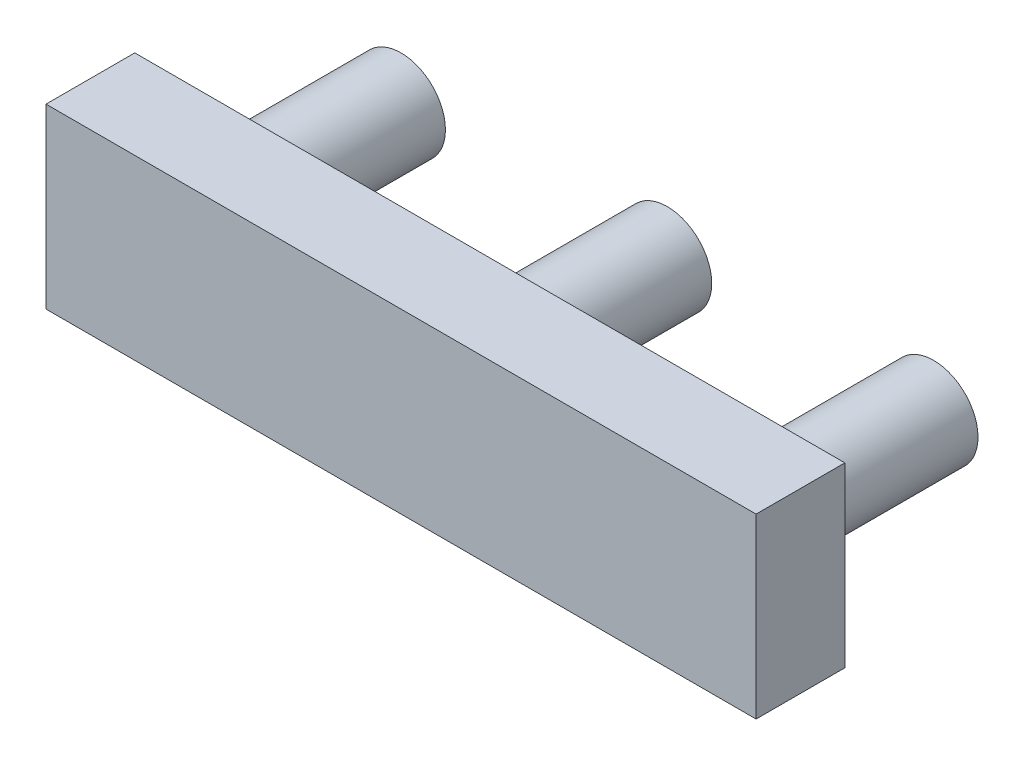
SolidWorks part; units mm, degrees
ref_plane "Front Plane" through (0, 0, 0) normal (0, 0, 1) x (1, 0, 0)
ref_plane "Top Plane" through (0, 0, 0) normal (0, 1, 0) x (1, 0, 0)
ref_plane "Right Plane" through (0, 0, 0) normal (1, 0, 0) x (0, 0, -1)
sketch "Sketch1" plane through (0, 0, 0) normal (0, 0, 1) x (1, 0, 0)
  circle A0 centre (0, 0) radius 3.175
  circle A1 centre (19.05, 0) radius 3.175
  circle A2 centre (-19.05, 0) radius 3.175
  point P7 (0, 0)
  point P9 (0, 0)
  dimension "D1" = 6.35
  dimension "D2" = 19.05
  dimension "D3" = 19.05
extrude "Boss-Extrude1" add sketch "Sketch1" along normal blind 12.7
sketch "Sketch2" plane through (0, 0, 12.7) normal (0, 0, 1) x (1, 0, 0)
  line L1 (-25.4, -6.35) -> (25.4, -6.35)
  line L2 (-25.4, -6.35) -> (-25.4, 6.35)
  line L3 (-25.4, 6.35) -> (25.4, 6.35)
  line L4 (25.4, -6.35) -> (25.4, 6.35)
  line L5 (-25.4, -6.35) -> (25.4, 6.35) construction
  line L6 (-25.4, 6.35) -> (25.4, -6.35) construction
  point P0 (0, 0)
  dimension "D1" = 12.7
  dimension "D2" = 50.8
extrude "Boss-Extrude2" add sketch "Sketch2" along normal blind 6.35
